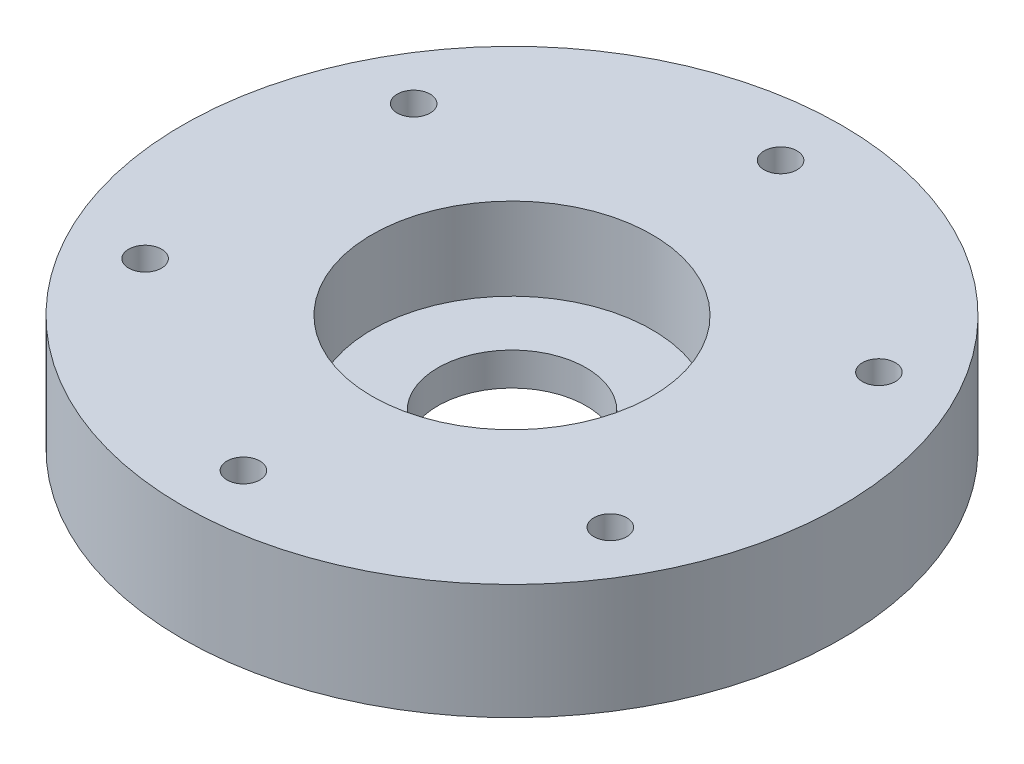
SolidWorks part; units mm, degrees
ref_plane "Front Plane" through (0, 0, 0) normal (0, 0, 1) x (1, 0, 0)
ref_plane "Top Plane" through (0, 0, 0) normal (0, 1, 0) x (1, 0, 0)
ref_plane "Right Plane" through (0, 0, 0) normal (1, 0, 0) x (0, 0, -1)
sketch "Sketch1" plane through (0, 0, 0) normal (0, 1, 0) x (1, 0, 0)
  line L0 (0, 0) -> (-31163.126, 0) construction
  line L1 (0, 0) -> (0, -31163.126) construction
  circle A0 centre (0, 0) radius 20
  dimension "D1" = 40
extrude "Boss-Extrude1" add sketch "Sketch1" along normal blind 7
sketch "Sketch2" plane through (0, 7, 0) normal (0, 1, 0) x (1, 0, 0)
  line L0 (0, 0) -> (-50000, 0) construction
  line L1 (0, 0) -> (0, -50000) construction
  circle A0 centre (0, 0) radius 8.5
  dimension "D1" = 17
extrude "Cut-Extrude1" cut sketch "Sketch2" against normal blind 5
sketch "Sketch3" plane through (0, 7, 0) normal (0, 1, 0) x (1, 0, 0)
  line L0 (0, 0) -> (-50000, 0) construction
  line L1 (0, 0) -> (0, -50000) construction
  circle A0 centre (0, 0) radius 4.5
  dimension "D1" = 9
extrude "Cut-Extrude2" cut sketch "Sketch3" against normal through all
sketch "Sketch4" plane through (0, 7, 0) normal (0, 1, 0) x (1, 0, 0)
  line L0 (0, 0) -> (-50000, 0) construction
  line L1 (0, 0) -> (0, -50000) construction
  circle A0 centre (0, 0) radius 16.3 construction
  circle A1 centre (0, 16.3) radius 1
  circle A2 centre (14.1162, 8.15) radius 1
  circle A3 centre (14.1162, -8.15) radius 1
  circle A4 centre (0, -16.3) radius 1
  circle A5 centre (-14.1162, -8.15) radius 1
  circle A6 centre (-14.1162, 8.15) radius 1
  point P22 (0, 0)
  dimension "D1" = 32.6
  dimension "D2" = 2
extrude "Cut-Extrude3" cut sketch "Sketch4" against normal blind 4
sketch "Sketch5" plane through (0, 3, 0) normal (0, 1, 0) x (1, 0, 0)
  line L0 (0, 0) -> (-50000, 0) construction
  line L1 (0, 0) -> (0, -50000) construction
  line L2 (12.1162, 6.9953) -> (14.1162, 5.8406)
  line L3 (0, 13.9906) -> (2, 15.1453)
  line L4 (2, 15.1453) -> (2, 17.4547)
  line L5 (2, 17.4547) -> (0, 18.6094)
  line L6 (0, 18.6094) -> (-2, 17.4547)
  line L7 (-2, 17.4547) -> (-2, 15.1453)
  line L8 (-2, 15.1453) -> (0, 13.9906)
  line L9 (14.1162, 5.8406) -> (16.1162, 6.9953)
  line L10 (16.1162, 6.9953) -> (16.1162, 9.3047)
  line L11 (16.1162, 9.3047) -> (14.1162, 10.4594)
  line L12 (14.1162, 10.4594) -> (12.1162, 9.3047)
  line L13 (12.1162, 9.3047) -> (12.1162, 6.9953)
  line L14 (12.1162, -6.9953) -> (12.1162, -9.3047)
  line L15 (12.1162, -9.3047) -> (14.1162, -10.4594)
  line L16 (14.1162, -10.4594) -> (16.1162, -9.3047)
  line L17 (16.1162, -9.3047) -> (16.1162, -6.9953)
  line L18 (16.1162, -6.9953) -> (14.1162, -5.8406)
  line L19 (14.1162, -5.8406) -> (12.1162, -6.9953)
  line L20 (0, -13.9906) -> (-2, -15.1453)
  line L21 (-2, -15.1453) -> (-2, -17.4547)
  line L22 (-2, -17.4547) -> (0, -18.6094)
  line L23 (0, -18.6094) -> (2, -17.4547)
  line L24 (2, -17.4547) -> (2, -15.1453)
  line L25 (2, -15.1453) -> (0, -13.9906)
  line L26 (-12.1162, -6.9953) -> (-14.1162, -5.8406)
  line L27 (-14.1162, -5.8406) -> (-16.1162, -6.9953)
  line L28 (-16.1162, -6.9953) -> (-16.1162, -9.3047)
  line L29 (-16.1162, -9.3047) -> (-14.1162, -10.4594)
  line L30 (-14.1162, -10.4594) -> (-12.1162, -9.3047)
  line L31 (-12.1162, -9.3047) -> (-12.1162, -6.9953)
  line L32 (-12.1162, 6.9953) -> (-12.1162, 9.3047)
  line L33 (-12.1162, 9.3047) -> (-14.1162, 10.4594)
  line L34 (-14.1162, 10.4594) -> (-16.1162, 9.3047)
  line L35 (-16.1162, 9.3047) -> (-16.1162, 6.9953)
  line L36 (-16.1162, 6.9953) -> (-14.1162, 5.8406)
  line L37 (-14.1162, 5.8406) -> (-12.1162, 6.9953)
  circle A0 centre (0, 16.3) radius 2 construction
  circle A1 centre (14.1162, 8.15) radius 2 construction
  circle A2 centre (14.1162, -8.15) radius 2 construction
  circle A3 centre (0, -16.3) radius 2 construction
  circle A4 centre (-14.1162, -8.15) radius 2 construction
  circle A5 centre (-14.1162, 8.15) radius 2 construction
  point P57 (0, 0)
  dimension "D1" = 4
extrude "Cut-Extrude4" cut sketch "Sketch5" along normal blind 1.7
